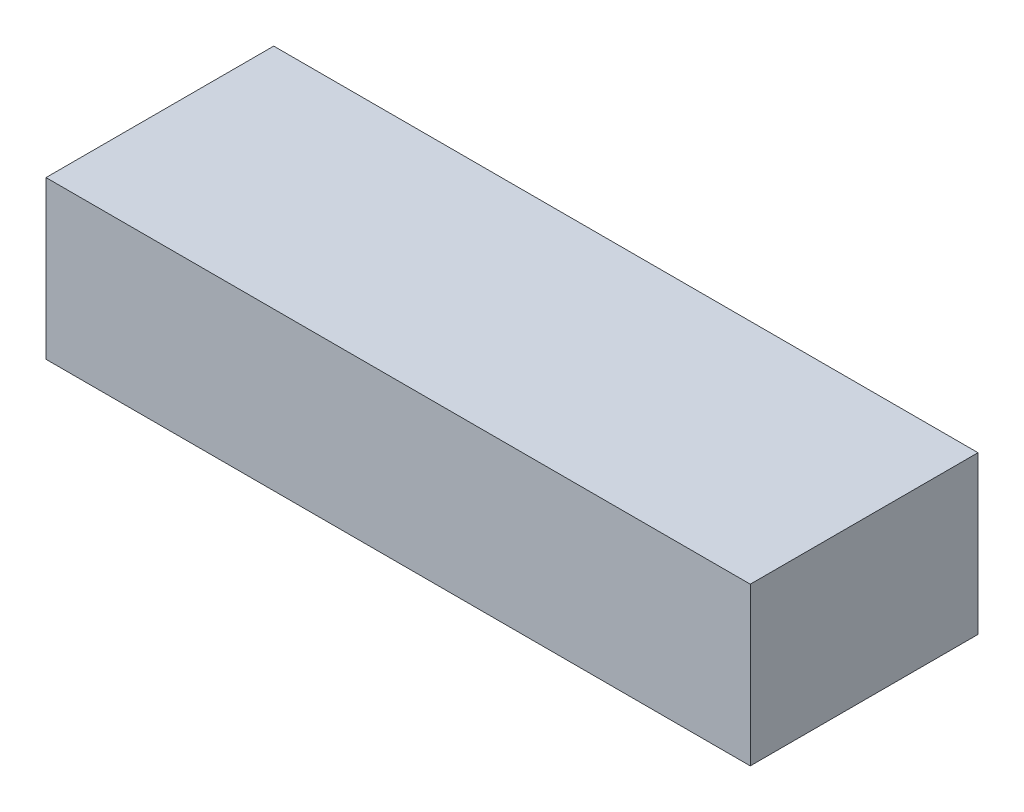
SolidWorks part; units mm, degrees
ref_plane "前基準面" through (0, 0, 0) normal (0, 0, 1) x (1, 0, 0)
ref_plane "上基準面" through (0, 0, 0) normal (0, 1, 0) x (1, 0, 0)
ref_plane "右基準面" through (0, 0, 0) normal (1, 0, 0) x (0, 0, -1)
sketch "草圖1" plane through (0, 0, 0) normal (0, 1, 0) x (1, 0, 0)
  line L1 (-52.575, -17) -> (52.575, -17)
  line L2 (-52.575, -17) -> (-52.575, 17)
  line L3 (-52.575, 17) -> (52.575, 17)
  line L4 (52.575, -17) -> (52.575, 17)
  line L5 (-52.575, -17) -> (52.575, 17) construction
  line L6 (-52.575, 17) -> (52.575, -17) construction
  point P0 (0, 0)
  dimension "D1" = 105.15
  dimension "D2" = 34
extrude "填料-伸長1" add sketch "草圖1" along normal blind 23.5
